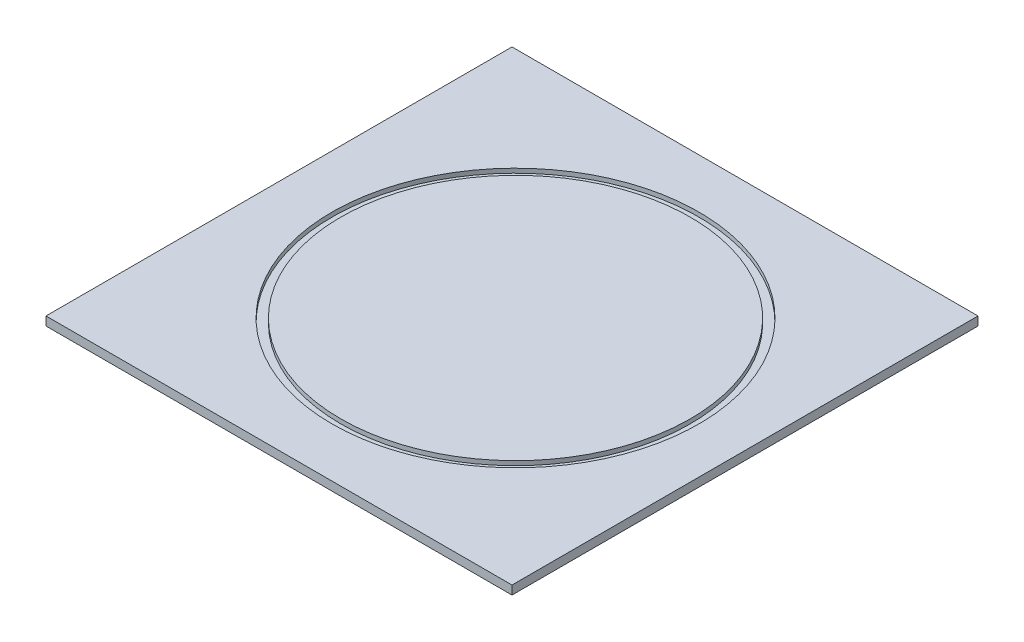
SolidWorks part; units mm, degrees
ref_plane "Front Plane" through (0, 0, 0) normal (0, 0, 1) x (1, 0, 0)
ref_plane "Top Plane" through (0, 0, 0) normal (0, 1, 0) x (1, 0, 0)
ref_plane "Right Plane" through (0, 0, 0) normal (1, 0, 0) x (0, 0, -1)
sketch "Sketch1" plane through (0, 0, 0) normal (0, 1, 0) x (1, 0, 0)
  line L1 (39.3959, 40) -> (-40.6041, 40)
  line L2 (39.3959, 40) -> (39.3959, -40)
  line L3 (39.3959, -40) -> (-40.6041, -40)
  line L4 (-40.6041, 40) -> (-40.6041, -40)
  line L5 (39.3959, 40) -> (-40.6041, -40) construction
  line L6 (39.3959, -40) -> (-40.6041, 40) construction
  dimension "D1" = 80
  dimension "D2" = 80
extrude "Boss-Extrude2" add sketch "Sketch1" along normal blind 1.5
sketch "Sketch2" plane through (0, 1.5, 0) normal (0, 1, 0) x (1, 0, 0)
  circle A0 centre (0, 0) radius 30
  circle A1 centre (0, 0) radius 31.5
extrude "Cut-Extrude2" cut sketch "Sketch2" against normal blind 0.75
